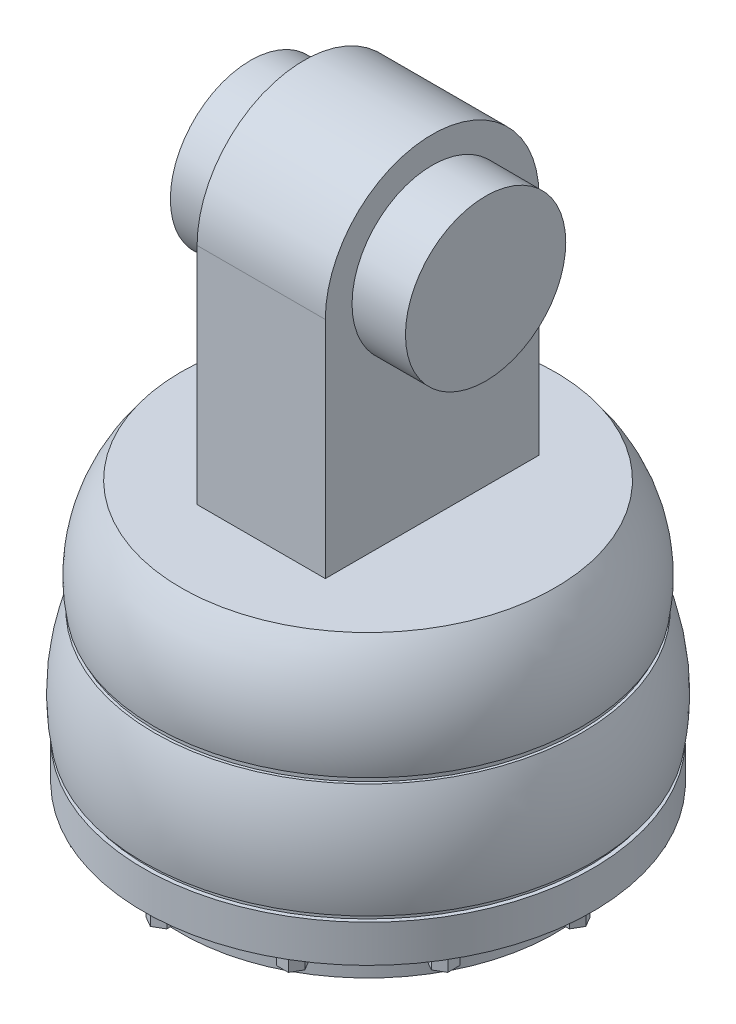
SolidWorks part; units mm, degrees
ref_plane "Front Plane" through (0, 0, 0) normal (0, 0, 1) x (1, 0, 0)
ref_plane "Top Plane" through (0, 0, 0) normal (0, 1, 0) x (1, 0, 0)
ref_plane "Right Plane" through (0, 0, 0) normal (1, 0, 0) x (0, 0, -1)
sketch "Sketch1" plane through (0, 0, 0) normal (0, 0, 1) x (1, 0, 0)
  line L0 (0, 0) -> (-35, 0)
  line L1 (0, 0) -> (0, -20)
  line L2 (0, -20) -> (-40, -20)
  arc A0 (-35, 0) -> (-40, -20) centre (-15.404, -15.524) ccw
  dimension "D4" = 25
  dimension "D1" = 35
  dimension "D2" = 40
  dimension "D3" = 20
revolve "Revolve1" add sketch "Sketch1" angle 360 about L1
sketch "Sketch2" plane through (0, -20, 0) normal (0, -1, 0) x (1, 0, 0)
  circle A0 centre (0, 0) radius 39.5
  dimension "D1" = 79
extrude "Boss-Extrude1" add sketch "Sketch2" along normal blind 1
sketch "Sketch3" plane through (0, 0, 0) normal (1, 0, 0) x (0, 0, -1)
  line L0 (0, -21) -> (-40, -21)
  line L1 (-39.5, -21) -> (39.5, -21) construction
  line L2 (0, -21) -> (0, -41)
  line L3 (0, -41) -> (-42, -41)
  arc A0 (-40, -21) -> (-42, -41) centre (-5.5677, -34.5432) ccw
  dimension "D4" = 37
  dimension "D1" = 40
  dimension "D2" = 42
  dimension "D3" = 20
revolve "Revolve3" add sketch "Sketch3" angle 360 about L2
sketch "Sketch4" plane through (0, -41, 0) normal (0, -1, 0) x (1, 0, 0)
  circle A0 centre (0, 0) radius 41.25
  dimension "D1" = 82.5
extrude "Boss-Extrude2" add sketch "Sketch4" along normal blind 1
sketch "Sketch5" plane through (0, -42, 0) normal (0, -1, 0) x (1, 0, 0)
  circle A0 centre (0, 0) radius 42
  dimension "D1" = 84
extrude "Boss-Extrude3" add sketch "Sketch5" along normal blind 7
sketch "Sketch6" plane through (0, -49, 0) normal (0, -1, 0) x (1, 0, 0)
  circle A0 centre (0, 0) radius 35
  dimension "D1" = 70
extrude "Boss-Extrude4" add sketch "Sketch6" along normal blind 7
sketch "Sketch7" plane through (0, -49, 0) normal (0, -1, 0) x (1, 0, 0)
  line L0 (35, 0) -> (42, 0) construction
  line L1 (37.9524, 0.9486) -> (37.4047, 0)
  line L2 (36.25, 0) -> (37.375, -1.9486)
  line L3 (37.375, -1.9486) -> (39.625, -1.9486)
  line L4 (39.625, -1.9486) -> (40.75, 0)
  line L5 (40.75, 0) -> (39.625, 1.9486)
  line L6 (39.625, 1.9486) -> (37.375, 1.9486)
  line L7 (37.375, 1.9486) -> (36.25, 0)
  line L8 (37.4047, 0) -> (37.9524, -0.9486)
  line L9 (37.9524, -0.9486) -> (39.0476, -0.9486)
  line L10 (39.0476, -0.9486) -> (39.5953, 0)
  line L11 (39.5953, 0) -> (39.0476, 0.9486)
  line L12 (39.0476, 0.9486) -> (37.9524, 0.9486)
  circle A0 centre (0, 0) radius 35 construction
  circle A1 centre (0, 0) radius 35 construction
  circle A2 centre (0, 0) radius 42 construction
  circle A3 centre (38.5, 0) radius 1.9486 construction
  dimension "D1" = 4.5
  dimension "D2" = 1
extrude "Boss-Extrude5" add sketch "Sketch7" along normal blind 3
pattern_circular "CirPattern1" count 12 over 360 about axis through (0, 0, 0) along (0, 1, 0) of "Boss-Extrude5"
sketch "Sketch8" plane through (0, -56, 0) normal (0, -1, 0) x (1, 0, 0)
  circle A0 centre (0, 0) radius 15
  dimension "D1" = 30
extrude "Boss-Extrude6" add sketch "Sketch8" along normal blind 10
sketch "Sketch9" plane through (0, 0, 0) normal (0, 1, 0) x (1, 0, 0)
  line L1 (12, 20) -> (-12, 20)
  line L2 (12, 20) -> (12, -20)
  line L3 (12, -20) -> (-12, -20)
  line L4 (-12, 20) -> (-12, -20)
  line L5 (12, 20) -> (-12, -20) construction
  line L6 (12, -20) -> (-12, 20) construction
  point P0 (0, 0)
  dimension "D1" = 24
  dimension "D2" = 40
extrude "Boss-Extrude7" add sketch "Sketch9" along normal blind 42
sketch "Sketch10" plane through (12, 0, 0) normal (1, 0, 0) x (0, 0, -1)
  line L0 (-20, 42) -> (20, 42) construction
  line L1 (-20, 42) -> (20, 42)
  arc A0 (20, 42) -> (-20, 42) centre (0, 42) ccw
extrude "Boss-Extrude8" add sketch "Sketch10" against normal up to vertex
sketch "Sketch11" plane through (12, 0, 0) normal (1, 0, 0) x (0, 0, -1)
  circle A0 centre (0, 42) radius 15
  dimension "D1" = 30
extrude "Boss-Extrude9" add sketch "Sketch11" along normal blind 10
sketch "Sketch12" plane through (-12, 0, 0) normal (-1, 0, 0) x (0, 0, 1)
  circle A0 centre (0, 42) radius 15
  dimension "D1" = 30
extrude "Boss-Extrude10" add sketch "Sketch12" along normal blind 10
